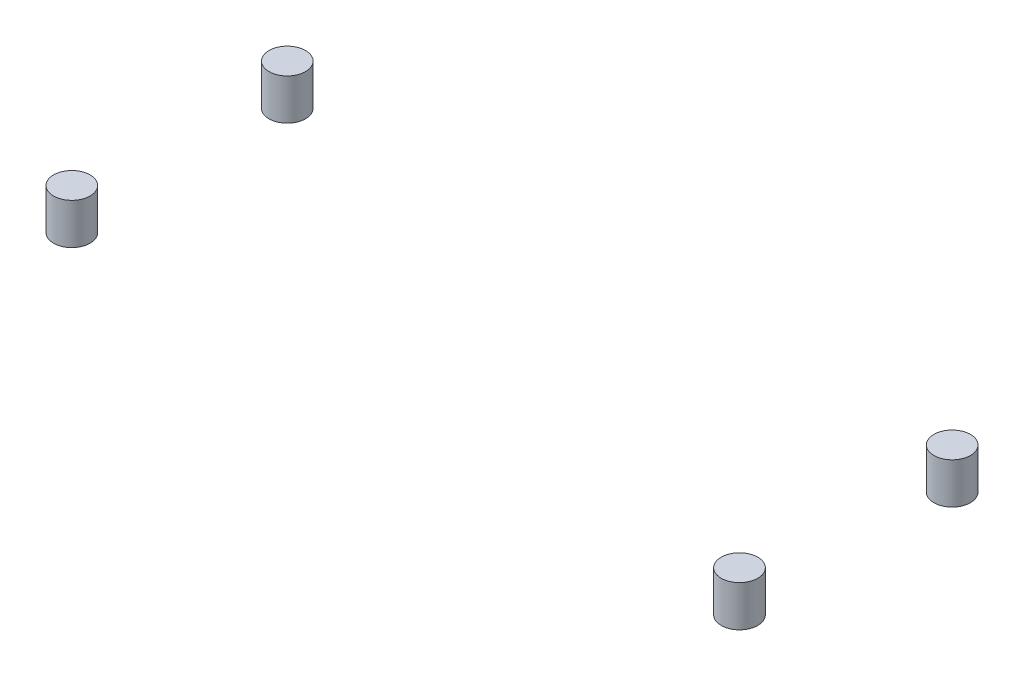
SolidWorks part; units mm, degrees
ref_plane "Front Plane" through (0, 0, 0) normal (0, 0, 1) x (1, 0, 0)
ref_plane "Top Plane" through (0, 0, 0) normal (0, 1, 0) x (1, 0, 0)
ref_plane "Right Plane" through (0, 0, 0) normal (1, 0, 0) x (0, 0, -1)
sketch "Sketch1" plane through (0, 118.1729, 0) normal (0, 1, 0) x (1, 0, 0)
  circle A0 centre (152.2016, -98.6751) radius 2.5
  circle A1 centre (61.2696, -98.6751) radius 2.5
  circle A2 centre (61.2696, -128.1391) radius 2.5
  circle A3 centre (152.2016, -127.7581) radius 2.5
  point P12 (0, 0)
  point P13 (61.2696, -98.6751)
  point P14 (0, 0)
  point P15 (0, 0)
  dimension "D1" = 5
  dimension "D2" = 5
  dimension "D3" = 5
  dimension "D4" = 5
extrude "Boss-Extrude1" add sketch "Sketch1" along normal blind 5.6
